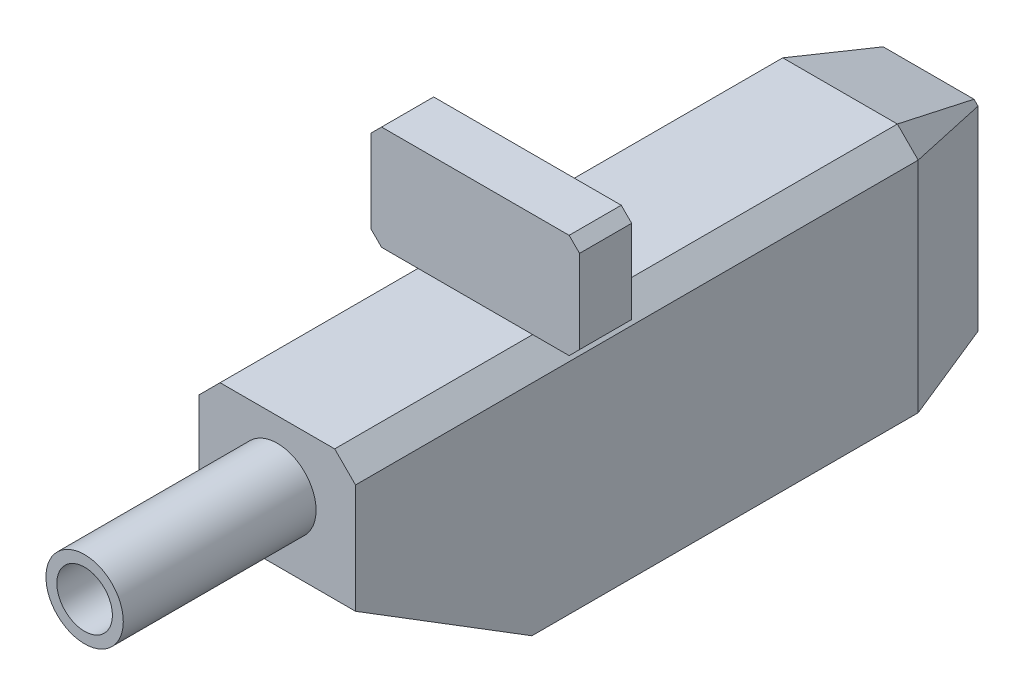
SolidWorks part; units mm, degrees
ref_plane "Front Plane" through (0, 0, 0) normal (0, 0, 1) x (1, 0, 0)
ref_plane "Top Plane" through (0, 0, 0) normal (0, 1, 0) x (1, 0, 0)
ref_plane "Right Plane" through (0, 0, 0) normal (1, 0, 0) x (0, 0, -1)
sketch "Sketch1" plane through (0, 0, 0) normal (0, 0, 1) x (1, 0, 0)
  line L9 (-11, 25) -> (-15, 21)
  line L10 (-11, 25) -> (11, 25)
  line L11 (-15, 21) -> (-15, -21)
  line L12 (-11, -25) -> (11, -25)
  line L13 (15, 21) -> (15, -21)
  line L14 (-15, 25) -> (15, -25) construction
  line L15 (-15, -25) -> (15, 25) construction
  line L16 (11, 25) -> (15, 21)
  line L17 (15, -21) -> (11, -25)
  line L18 (-15, -21) -> (-11, -25)
  point P0 (0, 0)
  dimension "D1" = 50
  dimension "D2" = 30
extrude "Boss-Extrude1" add sketch "Sketch1" along normal blind 108
sketch "Sketch2" plane through (0, 0, 108) normal (0, 0, 1) x (1, 0, 0)
  circle A0 centre (0, 13.0036) radius 5.3324
  circle A1 centre (0, 13.0036) radius 7.4243
  point P3 (0, 13.0036)
  dimension "D1" = 10.6649
  dimension "D2" = 14.8486
extrude "Boss-Extrude2" add sketch "Sketch2" along normal blind 37
ref_plane "Plane1" through (0, 0, 70) normal (0, 0, -1) x (-1, 0, 0)
sketch "Sketch3" plane through (0, 0, 70) normal (0, 0, -1) x (-1, 0, 0)
  line L0 (-11, 25) -> (11, 25) construction
  line L1 (-18, 45) -> (18, 45)
  line L2 (-20, 43) -> (-20, 27)
  line L3 (-18, 25) -> (18, 25)
  line L4 (20, 43) -> (20, 27)
  line L5 (-20, 45) -> (20, 25) construction
  line L6 (-20, 25) -> (20, 45) construction
  line L7 (-18, 45) -> (-20, 43)
  line L8 (18, 45) -> (20, 43)
  line L9 (20, 27) -> (18, 25)
  line L10 (-20, 27) -> (-18, 25)
  point P0 (0, 35)
  dimension "D1" = 20
  dimension "D2" = 40
extrude "Boss-Extrude3" add sketch "Sketch3" along normal blind 10
sketch "Sketch4" plane through (-15, 0, 0) normal (-1, 0, 0) x (0, 0, 1)
  line L0 (108, 0) -> (67.6856, -25)
  line L1 (108, 21) -> (108, -21) construction
  line L4 (108, -25) -> (0, -25) construction
  line L5 (67.6856, -25) -> (108, -25)
  line L6 (108, -25) -> (108, 0)
  point P4 (108.9687, -45.8263)
  point P5 (205, 19.542)
  point P7 (205, 0)
  point P11 (0, 0)
  point P12 (0, 0)
  point P13 (0, 0)
  point P14 (0, 0)
  point P15 (67.6856, -25)
extrude "Cut-Extrude1" cut sketch "Sketch4" against normal up to next
sketch "Sketch5" plane through (-28.5173, 0, 0) normal (0, 0, -1) x (-1, 0, 0)
  line L4 (-43.5173, 21) -> (-39.5173, 25)
  line L5 (-43.5173, -21) -> (-43.5173, 21) construction
  line L6 (-39.5173, 25) -> (-17.5173, 25)
  line L7 (-17.5173, 25) -> (-13.5173, 21)
  line L8 (-13.5173, 21) -> (-13.5173, -21)
  line L9 (-13.5173, -21) -> (-17.5173, -25)
  line L10 (-17.5173, -25) -> (-39.5173, -25)
  line L11 (-39.5173, -25) -> (-43.5173, -21)
  line L12 (-43.5173, -21) -> (-43.5173, 21)
extrude "Boss-Extrude5" add sketch "Sketch5" along normal blind 17 draft 18
